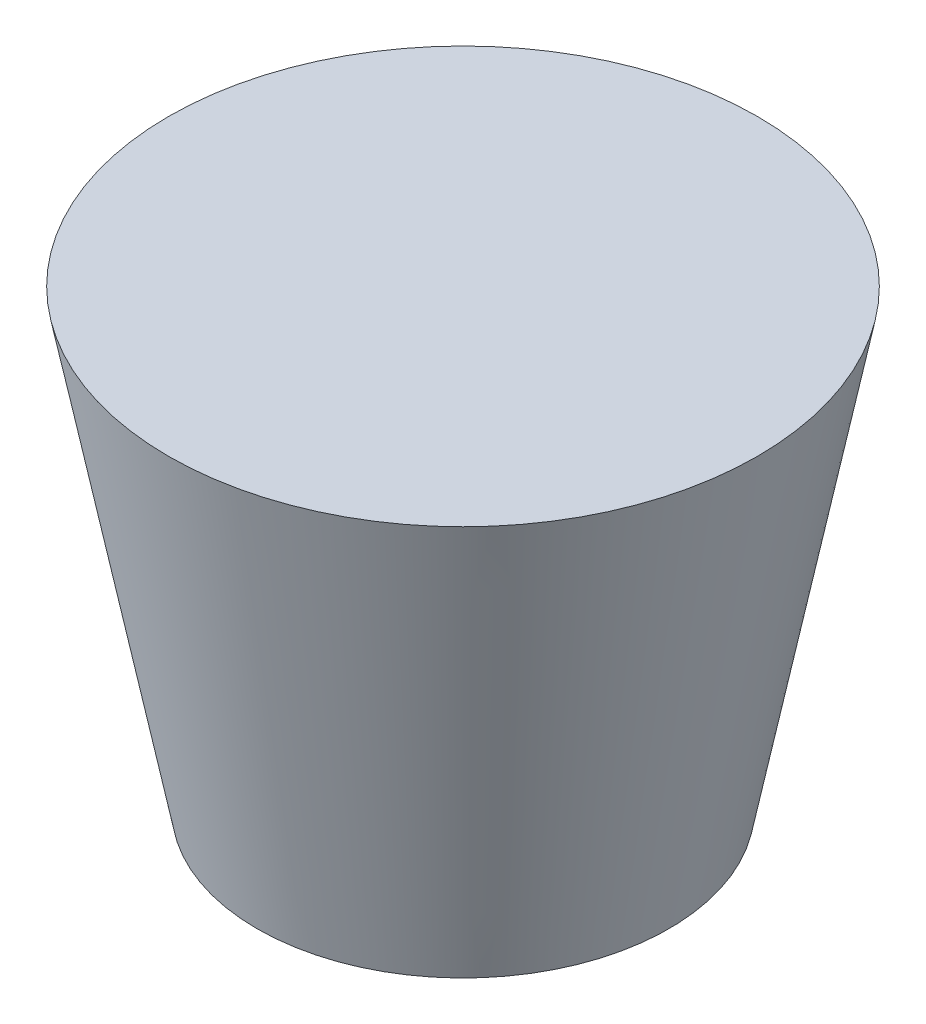
SolidWorks part; units mm, degrees
ref_plane "Front Plane" through (0, 0, 0) normal (0, 0, 1) x (1, 0, 0)
ref_plane "Top Plane" through (0, 0, 0) normal (0, 1, 0) x (1, 0, 0)
ref_plane "Right Plane" through (0, 0, 0) normal (1, 0, 0) x (0, 0, -1)
sketch "Sketch1" plane through (0, 0, 0) normal (0, 0, 1) x (1, 0, 0)
  line L0 (0, 93.9867) -> (0, -160.0133) construction
  line L1 (0, 75.122) -> (143.5066, 75.122)
  line L2 (143.5066, 75.122) -> (100.3873, -145.8647)
  line L3 (100.3873, -145.8647) -> (0, -145.8647)
  dimension "D1" = 254
revolve "Revolve-Thin1" add sketch "Sketch1" angle 360 about L0
